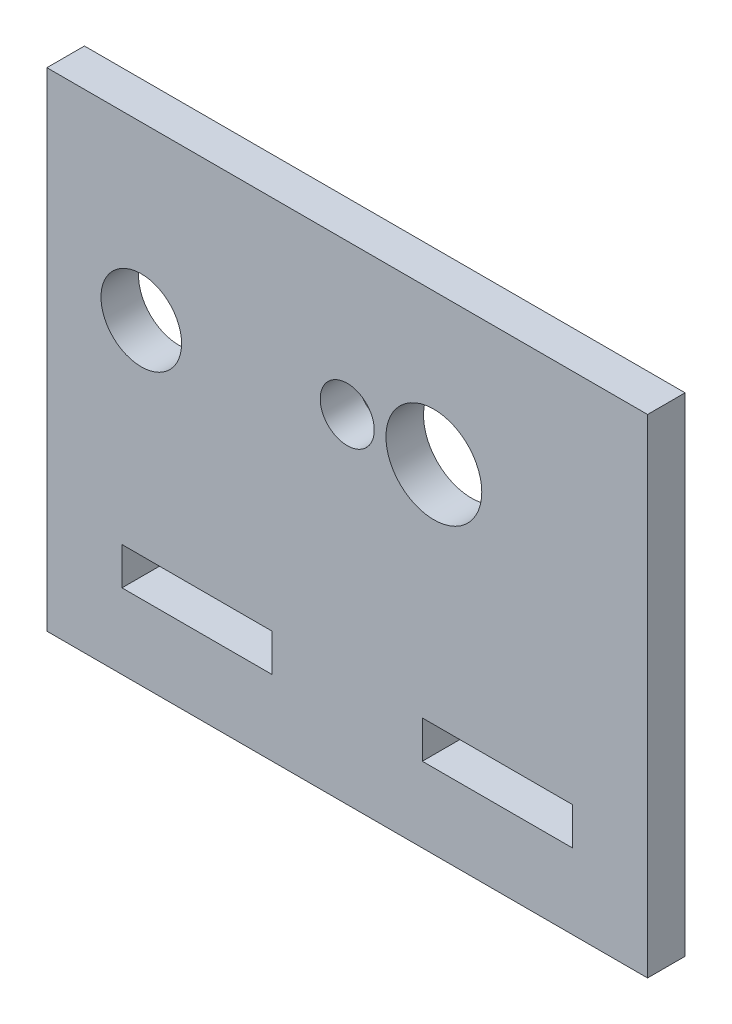
SolidWorks part; units mm, degrees
ref_plane "Front Plane" through (0, 0, 0) normal (0, 0, 1) x (1, 0, 0)
ref_plane "Top Plane" through (0, 0, 0) normal (0, 1, 0) x (1, 0, 0)
ref_plane "Right Plane" through (0, 0, 0) normal (1, 0, 0) x (0, 0, -1)
sketch "Sketch1" plane through (0, 0, 0) normal (0, 0, 1) x (1, 0, 0)
  line L3 (0, 0) -> (0, 41.275)
  line L4 (0, 41.275) -> (50.8, 41.275)
  line L5 (50.8, 41.275) -> (50.8, 0)
  line L8 (25.4, 28.575) -> (25.4, 41.275) construction
  line L9 (0, 0) -> (50.8, 0)
  line L11 (6.35, 6.35) -> (19.05, 6.35)
  line L12 (6.35, 6.35) -> (6.35, 9.525)
  line L13 (6.35, 9.525) -> (19.05, 9.525)
  line L14 (19.05, 6.35) -> (19.05, 9.525)
  line L15 (31.75, 6.35) -> (44.45, 6.35)
  line L16 (31.75, 6.35) -> (31.75, 9.525)
  line L17 (31.75, 9.525) -> (44.45, 9.525)
  line L18 (44.45, 6.35) -> (44.45, 9.525)
  circle A0 centre (25.4, 28.575) radius 2.286
  circle A1 centre (7.9815, 26.7618) radius 3.4077
  circle A2 centre (32.7273, 28.575) radius 4.0517
  dimension "D5" = 4.572
  dimension "D1" = 12.7
  dimension "D2" = 3.175
  dimension "D3" = 12.7
  dimension "D4" = 12.7
  dimension "D6" = 6.35
  dimension "D7" = 50.8
  dimension "D8" = 6.35
  dimension "D9" = 19.05
extrude "Boss-Extrude1" add sketch "Sketch1" along normal blind 3.175
